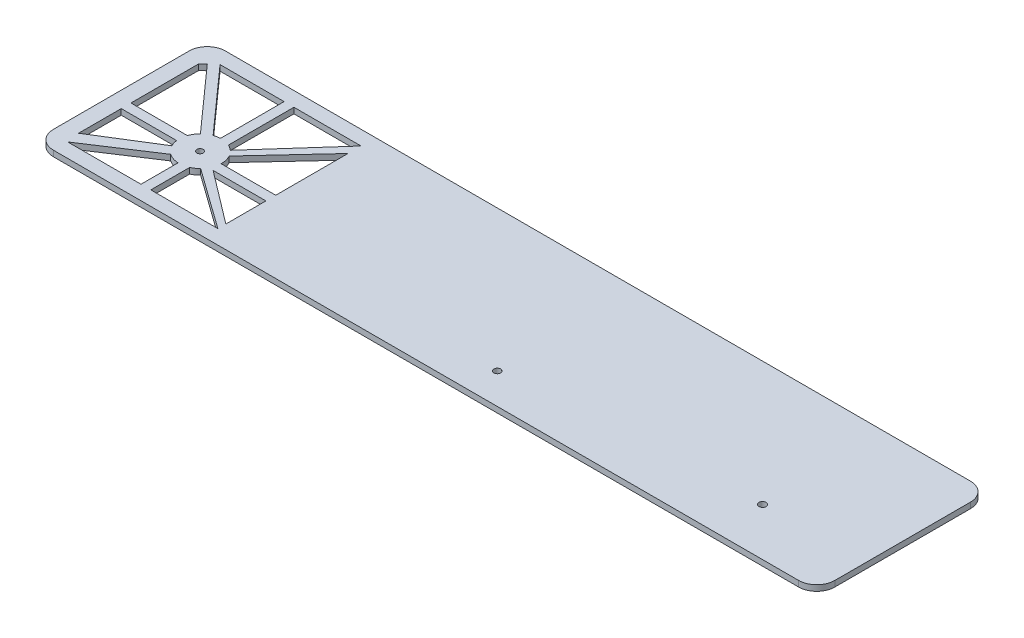
SolidWorks part; units mm, degrees
ref_plane "Front" through (0, 0, 0) normal (0, 0, 1) x (1, 0, 0)
ref_plane "Top" through (0, 0, 0) normal (0, 1, 0) x (1, 0, 0)
ref_plane "Right" through (0, 0, 0) normal (1, 0, 0) x (0, 0, -1)
sketch "Sketch1" plane through (0, 0, 0) normal (0, 1, 0) x (1, 0, 0)
  line L1 (-2.1325, 0) -> (429.6675, 0)
  line L2 (-2.1325, 0) -> (-2.1325, 95)
  line L3 (-2.1325, 95) -> (429.6675, 95)
  line L4 (429.6675, 0) -> (429.6675, 95)
  circle A0 centre (48.8675, 40.0503) radius 1.7702
  circle A4 centre (236.1694, 16.9951) radius 1.9029
  circle A5 centre (373.3432, 26.3683) radius 2
  dimension "D1" = 95
  dimension "D2" = 431.8
extrude "Boss-Extrude1" add sketch "Sketch1" along normal blind 3.175
fillet "Fillet1" radius 10 4 edges at (429.6675, 1.5875, -95) (429.6675, 1.5875, 0) (-2.1325, 1.5875, 0) (-2.1325, 1.5875, -95)
sketch "Sketch10" plane through (0, 0, 0) normal (0, -1, 0) x (1, 0, 0)
  circle A0 centre (48.8675, -40.0503) radius 9.1799
extrude "Boss-Extrude3" add sketch "Sketch10" against normal blind 3.175
sketch "Sketch11" plane through (0, 3.175, 0) normal (0, 1, 0) x (1, 0, 0)
  circle A0 centre (48.9393, 40.0886) radius 1.7706
extrude "Cut-Extrude5" cut sketch "Sketch11" against normal blind 3.175
sketch "Sketch12" plane through (0, 3.175, 0) normal (0, 1, 0) x (1, 0, 0)
  line L0 (48.3413, 47.3347) -> (48.3413, 86.998)
  line L1 (48.3413, 86.998) -> (12.9393, 86.998)
  line L2 (12.9393, 86.998) -> (48.3413, 47.3347)
  line L3 (44.6049, 43.9998) -> (9.2029, 83.6631)
  line L4 (9.2029, 83.6631) -> (6.6849, 81.4156)
  line L5 (6.6849, 81.4156) -> (6.6849, 43.9998)
  line L6 (6.6849, 43.9998) -> (44.6049, 43.9998)
  line L7 (44.6049, 38.6481) -> (6.6849, 38.6481)
  line L8 (6.6849, 38.6481) -> (6.6849, 15.0468)
  line L9 (6.6849, 15.0468) -> (44.6049, 38.6481)
  line L10 (7.8532, 7.8939) -> (48.3413, 34.4385)
  line L11 (48.3413, 34.4385) -> (48.3413, 7.8939)
  line L12 (7.8532, 7.8939) -> (44.6049, 7.8939)
  line L13 (48.3413, 7.8939) -> (44.6049, 7.8939)
  line L15 (55.46, 47.3347) -> (90.8387, 86.998)
  line L16 (90.8387, 86.998) -> (55.46, 86.998)
  line L17 (53.7591, 86.998) -> (55.46, 86.998)
  line L18 (53.7591, 86.998) -> (53.7591, 45.8712)
  line L19 (53.7591, 45.8712) -> (55.46, 47.3347)
  line L22 (90.8387, 39.859) -> (90.8387, 79.8303)
  line L26 (53.7591, 34.4385) -> (53.7591, 7.8939)
  line L27 (53.7591, 7.8939) -> (90.8387, 7.8939)
  line L28 (90.8387, 7.8939) -> (53.7591, 34.4385)
  line L29 (55.8337, 42.0953) -> (55.8337, 39.859)
  line L30 (90.8387, 79.8303) -> (55.8337, 42.0953)
  line L31 (55.8337, 39.859) -> (90.8387, 39.859)
  line L32 (61.6479, 34.4385) -> (90.8387, 12.2904)
  line L33 (90.8387, 12.2904) -> (90.8387, 34.4385)
  line L35 (90.8387, 34.4385) -> (61.6479, 34.4385)
extrude "Cut-Extrude6" cut sketch "Sketch12" against normal blind 3.175
sketch "Sketch13" plane through (0, 3.175, 0) normal (0, 1, 0) x (1, 0, 0)
  circle A0 centre (48.9393, 40.0886) radius 11.7419
extrude "Boss-Extrude4" add sketch "Sketch13" against normal blind 3.175
sketch "Sketch14" plane through (0, 3.175, 0) normal (0, 1, 0) x (1, 0, 0)
  circle A0 centre (48.8704, 40.0182) radius 1.7623
extrude "Cut-Extrude8" cut sketch "Sketch14" against normal blind 3.175
